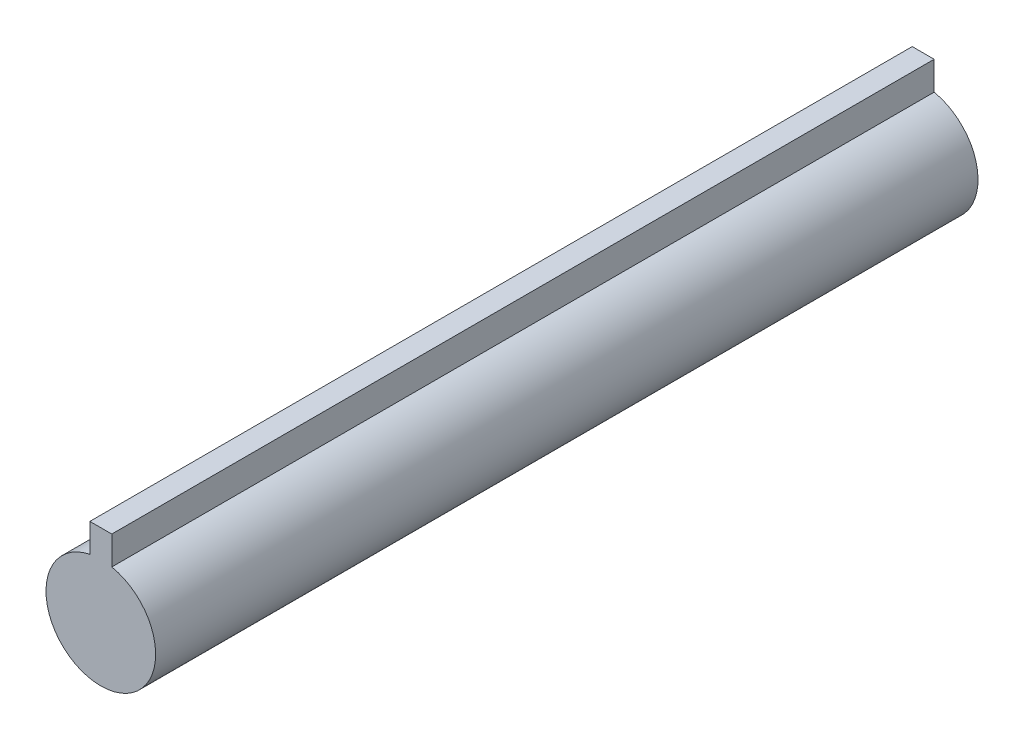
SolidWorks part; units mm, degrees
ref_plane "前视基准面" through (0, 0, 0) normal (0, 0, 1) x (1, 0, 0)
ref_plane "上视基准面" through (0, 0, 0) normal (0, 1, 0) x (1, 0, 0)
ref_plane "右视基准面" through (0, 0, 0) normal (1, 0, 0) x (0, 0, -1)
sketch "草图1" plane through (0, 0, 0) normal (0, 0, 1) x (1, 0, 0)
  line L1 (0, 1.5) -> (0.2, 1.5)
  line L2 (0, 1.5) -> (-0.2, 1.5)
  line L3 (-0.2, 1.5) -> (-0.2, 0.9798)
  line L4 (0.2, 1.5) -> (0.2, 0.9798)
  arc A0 (-0.2, 0.9798) -> (0.2, 0.9798) centre (0, 0) ccw
  dimension "D1" = 2
  dimension "D2" = 1.5
  dimension "D3" = 0.2
  dimension "D4" = 0.2
extrude "凸台-拉伸1" add sketch "草图1" along normal blind 15
